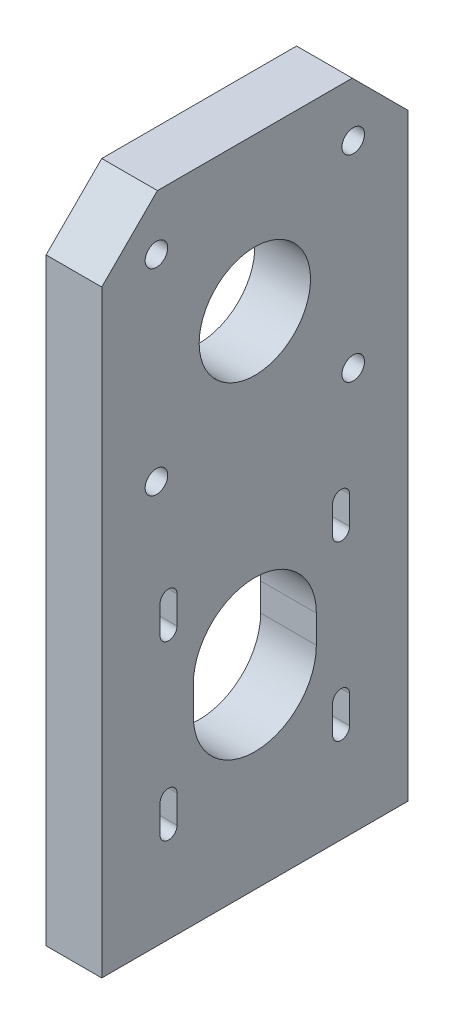
SolidWorks part; units mm, degrees
ref_plane "前视基准面" through (0, 0, 0) normal (0, 0, 1) x (1, 0, 0)
ref_plane "上视基准面" through (0, 0, 0) normal (0, 1, 0) x (1, 0, 0)
ref_plane "右视基准面" through (0, 0, 0) normal (1, 0, 0) x (0, 0, -1)
sketch "草图1" plane through (0, 0, 0) normal (0, 1, 0) x (1, 0, 0)
  line L6 (0, 27.5) -> (-20, 27.5)
  line L7 (-20, 27.5) -> (-20, -27.5)
  line L8 (-20, -27.5) -> (0, -27.5)
  line L9 (0, 0) -> (-20, 0) construction
  line L10 (-15, 23.75) -> (-15, -23.75) construction
  line L11 (-20, 27.5) -> (-30, 27.5)
  line L12 (-20, 27.5) -> (-20, -27.5)
  line L13 (-20, -27.5) -> (-30, -27.5)
  line L14 (-30, 27.5) -> (-30, -27.5)
  circle A1 centre (0, 0) radius 10.25 construction
  circle A2 centre (0, 10.25) radius 1.5
  circle A3 centre (8.8768, 5.125) radius 1.5
  circle A4 centre (8.8768, -5.125) radius 1.5
  circle A5 centre (0, -10.25) radius 1.5
  circle A6 centre (-15, 23.75) radius 2
  circle A7 centre (-15, -23.75) radius 2
  arc A8 (0, 27.5) -> (0, -27.5) centre (0, 0) cw
  circle A9 centre (-8.8768, -5.125) radius 1.5
  circle A10 centre (-8.8768, 5.125) radius 1.5
  point P14 (-15, 0)
  point P23 (0, 0)
  dimension "D1" = 55
  dimension "D4" = 20.5
  dimension "D5" = 3
  dimension "D7" = 4
  dimension "D2" = 20
  dimension "D3" = 10
  dimension "D8" = 47.5
  dimension "D9" = 5
  dimension "D6" = 6
extrude "凸台-拉伸1" add sketch "草图1" along normal blind 10
sketch "草图2" plane through (0, 10, 0) normal (0, 1, 0) x (1, 0, 0)
  line L0 (0, 27.5) -> (-30, 27.5) construction
  line L1 (-30, -27.5) -> (-20, -27.5)
  line L2 (-30, -27.5) -> (-30, 27.5)
  line L3 (-30, 27.5) -> (-20, 27.5)
  line L4 (-20, -27.5) -> (-20, 27.5)
  dimension "D1" = 10
extrude "凸台-拉伸2" add sketch "草图2" along normal blind 117.5
sketch "草图3" plane through (-30, 0, 0) normal (-1, 0, 0) x (0, 0, 1)
  line L0 (0, 0) -> (0, 45) construction
  line L1 (-27.5, 0) -> (27.5, 0) construction
  line L2 (0, 45) -> (0, 100) construction
  line L3 (0, 100) -> (0, 127.5) construction
  line L4 (-15.5, 29.5) -> (15.5, 29.5) construction
  line L5 (-15.5, 29.5) -> (-15.5, 60.5) construction
  line L6 (-15.5, 60.5) -> (15.5, 60.5) construction
  line L7 (15.5, 29.5) -> (15.5, 60.5) construction
  line L8 (-15.5, 29.5) -> (15.5, 60.5) construction
  line L9 (-15.5, 60.5) -> (15.5, 29.5) construction
  line L10 (-17.6777, 82.3223) -> (17.6777, 82.3223) construction
  line L11 (-17.6777, 82.3223) -> (-17.6777, 117.6777) construction
  line L12 (-17.6777, 117.6777) -> (17.6777, 117.6777) construction
  line L13 (17.6777, 82.3223) -> (17.6777, 117.6777) construction
  line L14 (-17.6777, 82.3223) -> (17.6777, 117.6777) construction
  line L15 (-17.6777, 117.6777) -> (17.6777, 82.3223) construction
  line L22 (-15.5, 60.5) -> (-15.5, 63) construction
  line L23 (-15.5, 63) -> (-15.5, 58) construction
  line L24 (-13.975, 63) -> (-13.975, 58)
  line L25 (-17.025, 63) -> (-17.025, 58)
  line L26 (-15.5, 32) -> (-15.5, 27) construction
  line L27 (-13.975, 32) -> (-13.975, 27)
  line L28 (-17.025, 32) -> (-17.025, 27)
  line L29 (15.5, 63) -> (15.5, 58) construction
  line L30 (13.975, 63) -> (13.975, 58)
  line L31 (17.025, 63) -> (17.025, 58)
  line L32 (15.5, 32) -> (15.5, 27) construction
  line L33 (13.975, 32) -> (13.975, 27)
  line L34 (17.025, 32) -> (17.025, 27)
  line L35 (0, 47.5) -> (0, 42.5) construction
  line L36 (11.05, 47.5) -> (11.05, 42.5)
  line L37 (-11.05, 47.5) -> (-11.05, 42.5)
  circle A5 centre (-17.6777, 117.6777) radius 2.025
  circle A6 centre (17.6777, 117.6777) radius 2.025
  circle A7 centre (17.6777, 82.3223) radius 2.025
  circle A8 centre (-17.6777, 82.3223) radius 2.025
  circle A9 centre (0, 100) radius 10
  arc A10 (-13.975, 63) -> (-17.025, 63) centre (-15.5, 63) ccw
  arc A11 (-17.025, 58) -> (-13.975, 58) centre (-15.5, 58) ccw
  arc A12 (-13.975, 32) -> (-17.025, 32) centre (-15.5, 32) ccw
  arc A13 (-17.025, 27) -> (-13.975, 27) centre (-15.5, 27) ccw
  arc A14 (13.975, 63) -> (17.025, 63) centre (15.5, 63) cw
  arc A15 (17.025, 58) -> (13.975, 58) centre (15.5, 58) cw
  arc A16 (13.975, 32) -> (17.025, 32) centre (15.5, 32) cw
  arc A17 (17.025, 27) -> (13.975, 27) centre (15.5, 27) cw
  arc A18 (11.05, 47.5) -> (-11.05, 47.5) centre (0, 47.5) ccw
  arc A19 (-11.05, 42.5) -> (11.05, 42.5) centre (0, 42.5) ccw
  point P10 (-15.5, 60.5)
  point P19 (-15.5, 29.5)
  point P47 (0, 45)
  point P51 (15.5, 60.5)
  point P58 (15.5, 29.5)
  dimension "D3" = 5
  dimension "D5" = 11.05
  dimension "D8" = 4.05
  dimension "D10" = 20
  dimension "D4" = 1.525
  dimension "D1" = 45
  dimension "D2" = 31
  dimension "D6" = 55
  dimension "D7" = 50
  dimension "D11" = 27.5
  dimension "D12" = 5
  dimension "D9" = 4
extrude "切除-拉伸1" cut sketch "草图3" against normal through all
sketch "草图5" plane through (-30, 0, 0) normal (-1, 0, 0) x (0, 0, 1)
  line L0 (-27.5, 117.5) -> (-17.5, 127.5)
  line L1 (-27.5, 127.5) -> (-27.5, 0) construction
  line L2 (-27.5, 127.5) -> (27.5, 127.5) construction
  line L3 (-27.5, 117.5) -> (-27.5, 127.5)
  line L4 (-27.5, 127.5) -> (-17.5, 127.5)
  line L5 (0, -31.625) -> (0, 31.625) construction
  line L6 (27.5, 117.5) -> (27.5, 127.5)
  line L7 (27.5, 117.5) -> (17.5, 127.5)
  line L8 (27.5, 127.5) -> (17.5, 127.5)
  dimension "D1" = 10
extrude "切除-拉伸2" cut sketch "草图5" against normal through all
sketch "草图6" plane through (0, 0, -27.5) normal (0, 0, -1) x (-1, 0, 0)
  line L1 (-27.5, 10) -> (30, 10)
  line L2 (-27.5, 10) -> (-27.5, 0)
  line L3 (-27.5, 0) -> (30, 0)
  line L4 (30, 10) -> (30, 0)
extrude "切除-拉伸3" cut sketch "草图6" against normal through all
sketch "草图7" plane through (0, 10, 0) normal (0, -1, 0) x (1, 0, 0)
  line L0 (-25, 27.5) -> (-25, 22.5) construction
  line L1 (-30, 27.5) -> (-20, 27.5) construction
  line L2 (-25, 22.5) -> (-25, 7.5) construction
  line L3 (-25, 7.5) -> (-25, -7.5) construction
  line L4 (-25, -7.5) -> (-25, -22.5) construction
  line L5 (-25, -22.5) -> (-25, -27.5) construction
  line L6 (-30, -27.5) -> (-20, -27.5) construction
  circle A0 centre (-25, 22.5) radius 1.65
  circle A1 centre (-25, 7.5) radius 1.65
  circle A2 centre (-25, -7.5) radius 1.65
  circle A3 centre (-25, -22.5) radius 1.65
  dimension "D1" = 3.3
  dimension "D2" = 5
extrude "切除-拉伸4" cut sketch "草图7" against normal blind 12
sketch "草图8" plane through (-20, 0, 0) normal (1, 0, 0) x (0, 0, -1)
  line L0 (-27.5, 10) -> (27.5, 10) construction
  line L1 (-15, 10) -> (15, 10)
  line L2 (-15, 10) -> (-15, 17)
  line L3 (-15, 17) -> (15, 17)
  line L4 (15, 10) -> (15, 17)
  point P6 (0, 10)
  dimension "D1" = 7
  dimension "D2" = 30
extrude "凸台-拉伸3" [suppressed] add sketch "草图8" along normal blind 5
sketch "草图9" [suppressed] plane through (0, 0, -15) normal (0, 0, -1) x (-1, 0, 0)
  line L0 (20, 17) -> (15, 12)
  line L1 (15, 10) -> (15, 17) construction
  line L2 (15, 12) -> (15, 17)
  line L3 (15, 17) -> (20, 17)
extrude "切除-拉伸5" [suppressed] cut sketch "草图9" against normal through all
